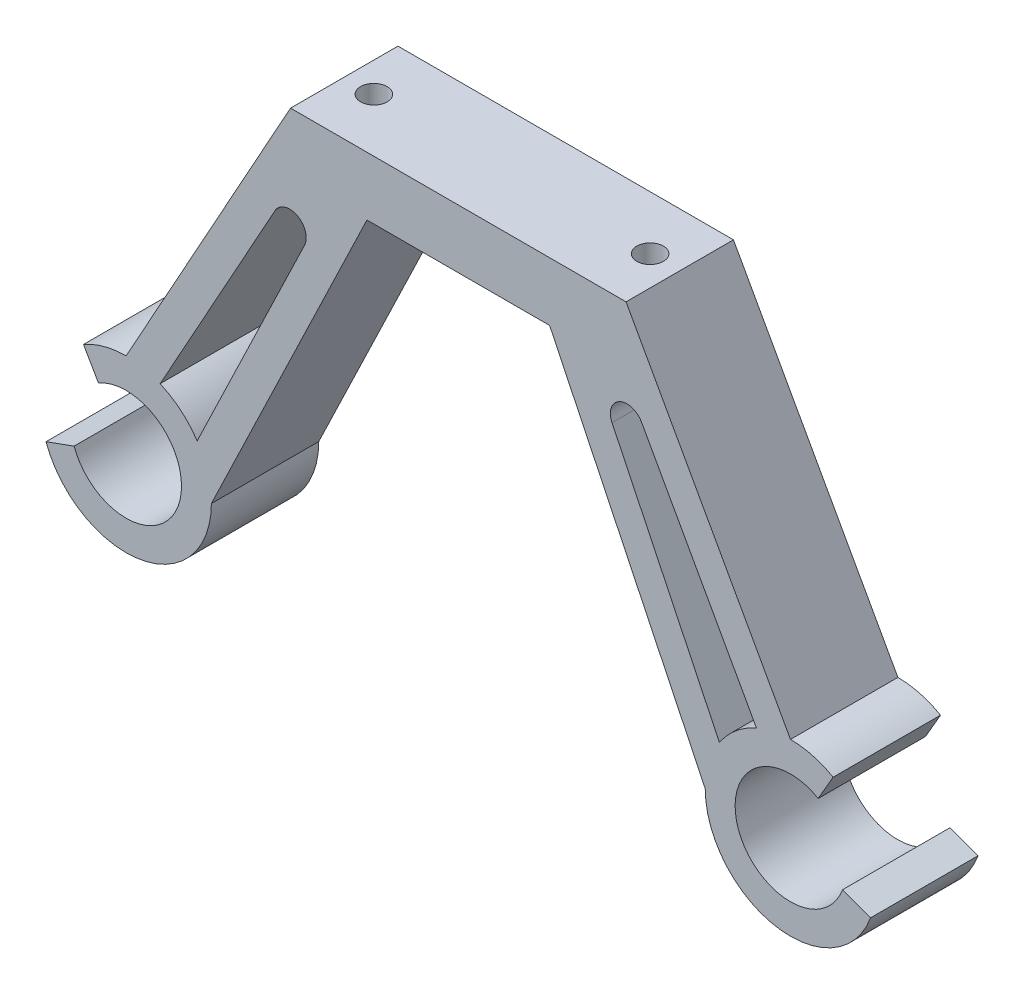
SolidWorks part; units mm, degrees
material "ABS PC"
ref_plane "Front Plane" through (0, 0, 0) normal (0, 0, 1) x (1, 0, 0)
ref_plane "Top Plane" through (0, 0, 0) normal (0, 1, 0) x (1, 0, 0)
ref_plane "Right Plane" through (0, 0, 0) normal (1, 0, 0) x (0, 0, -1)
sketch "Sketch1" plane through (0, 0, 0) normal (0, 0, 1) x (1, 0, 0)
  line L0 (-15.15, 19.9) -> (15.15, 19.9)
  line L1 (15.15, 19.9) -> (30, -6.9)
  line L2 (-15.15, 19.9) -> (-30, -6.9)
  line L3 (-22.3, -14.6) -> (-8.25, 14.6)
  line L4 (-8.25, 14.6) -> (8.25, 14.6)
  line L5 (8.25, 14.6) -> (22.3, -14.6)
  line L6 (-33.85, -7.9316) -> (-32.5, -10.2699)
  line L7 (-34.6985, -16.3101) -> (-37.2356, -17.2336)
  line L8 (33.85, -7.9316) -> (32.5, -10.2699)
  line L9 (34.6985, -16.3101) -> (37.2356, -17.2336)
  line L10 (0, -55) -> (0, 55) construction
  line L11 (-30, -14.6) -> (30, -14.6) construction
  line L12 (55, 0) -> (-55, 0) construction
  arc A0 (-37.2356, -17.2336) -> (-22.3, -14.6) centre (-30, -14.6) ccw
  arc A1 (33.85, -7.9316) -> (30, -6.9) centre (30, -14.6) ccw
  arc A2 (-34.6985, -16.3101) -> (-32.5, -10.2699) centre (-30, -14.6) ccw
  arc A3 (32.5, -10.2699) -> (34.6985, -16.3101) centre (30, -14.6) ccw
  arc A4 (22.3, -14.6) -> (37.2356, -17.2336) centre (30, -14.6) ccw
  arc A5 (-30, -6.9) -> (-33.85, -7.9316) centre (-30, -14.6) ccw
  point P12 (0, 19.9)
  point P21 (0, 14.6)
  point P22 (0, -14.6)
  point P33 (-15.275, 0)
  dimension "D2" = 5
  dimension "D3" = 2.7
  dimension "D1" = 5.3
  dimension "D4" = 30.3
  dimension "D5" = 16.5
  dimension "D6" = 34.5
  dimension "D7" = 80
  dimension "D8" = 80
  dimension "D9" = 60
  dimension "D10" = 20
extrude "Boss-Extrude1" add sketch "Sketch1" along normal mid plane 9.7
sketch "Sketch2" plane through (0, 0, 0) normal (0, 0, 1) x (1, 0, 0)
  line L0 (-26.9252, -7.5406) -> (-16.5462, 11.1905)
  line L1 (-13.8825, 9.8131) -> (-23.5821, -10.3455)
  line L2 (-15.15, 19.9) -> (-30, -6.9) construction
  line L3 (-22.3, -14.6) -> (-8.25, 14.6) construction
  line L4 (0, -5.335) -> (0, 5.335) construction
  line L5 (13.8825, 9.8131) -> (23.5821, -10.3455)
  line L6 (26.9252, -7.5406) -> (16.5462, 11.1905)
  arc A0 (-23.5821, -10.3455) -> (-26.9252, -7.5406) centre (-30, -14.6) ccw
  arc A2 (-13.8825, 9.8131) -> (-16.5462, 11.1905) centre (-15.2342, 10.4635) ccw
  arc A3 (13.8825, 9.8131) -> (16.5462, 11.1905) centre (15.2342, 10.4635) cw
  arc A4 (23.5821, -10.3455) -> (26.9252, -7.5406) centre (30, -14.6) cw
  dimension "D1" = 1.5
  dimension "D2" = 3
  dimension "D3" = 3
extrude "Cut-Extrude1" cut sketch "Sketch2" against normal through all both and the other way through all
sketch "Sketch3" plane through (0, 19.9, 0) normal (0, 1, 0) x (1, 0, 0)
  line L1 (-12.475, 0) -> (12.475, 0) construction
  line L2 (-23.21, 0) -> (23.21, 0) construction
  line L3 (0, -5.335) -> (0, 5.335) construction
  circle A0 centre (-12.475, 0) radius 1.2
  circle A1 centre (12.475, 0) radius 1.2
  point P5 (0, 0)
  dimension "D2" = 2.4
  dimension "D1" = 24.95
extrude "Cut-Extrude2" cut sketch "Sketch3" against normal blind 4
